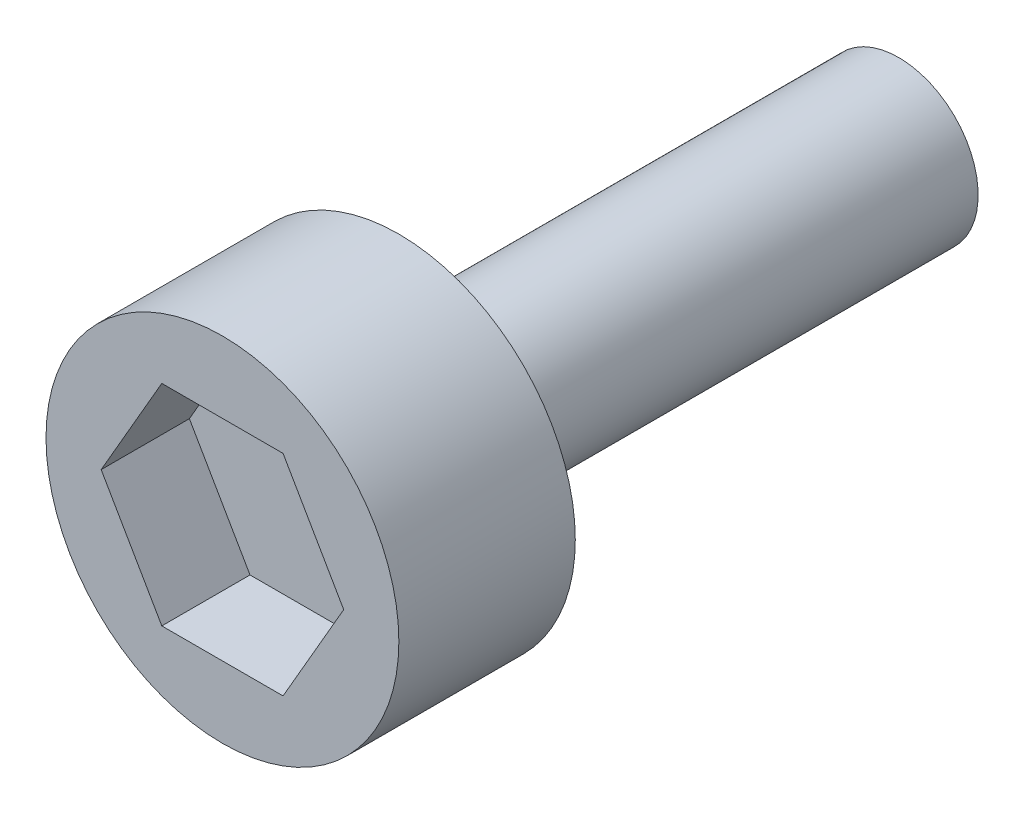
SolidWorks part; units mm, degrees
ref_plane "Front Plane" through (0, 0, 0) normal (0, 0, 1) x (1, 0, 0)
ref_plane "Top Plane" through (0, 0, 0) normal (0, 1, 0) x (1, 0, 0)
ref_plane "Right Plane" through (0, 0, 0) normal (1, 0, 0) x (0, 0, -1)
sketch "Sketch1" plane through (0, 0, 0) normal (0, 0, 1) x (1, 0, 0)
  circle A0 centre (0, 0) radius 3
  dimension "D1" = 6
extrude "Boss-Extrude1" add sketch "Sketch1" along normal blind 3
sketch "Sketch2" plane through (0, 0, 3) normal (0, 0, 1) x (1, 0, 0)
  line L1 (2.0619, 0) -> (1.031, 1.7857)
  line L2 (1.031, 1.7857) -> (-1.031, 1.7857)
  line L3 (-1.031, 1.7857) -> (-2.0619, 0)
  line L4 (-2.0619, 0) -> (-1.031, -1.7857)
  line L5 (-1.031, -1.7857) -> (1.031, -1.7857)
  line L6 (1.031, -1.7857) -> (2.0619, 0)
  circle A0 centre (0, 0) radius 1.7857 construction
extrude "Cut-Extrude1" cut sketch "Sketch2" against normal blind 1.5
sketch "Sketch4" plane through (0, 0, 0) normal (0, 0, -1) x (-1, 0, 0)
  circle A0 centre (0, 0) radius 1.35
  dimension "D1" = 2.7
sketch "Sketch5" plane through (0, 0, 0) normal (0, 0, -1) x (-1, 0, 0)
extrude "Boss-Extrude2" add sketch "Sketch4" along normal blind 8.5
